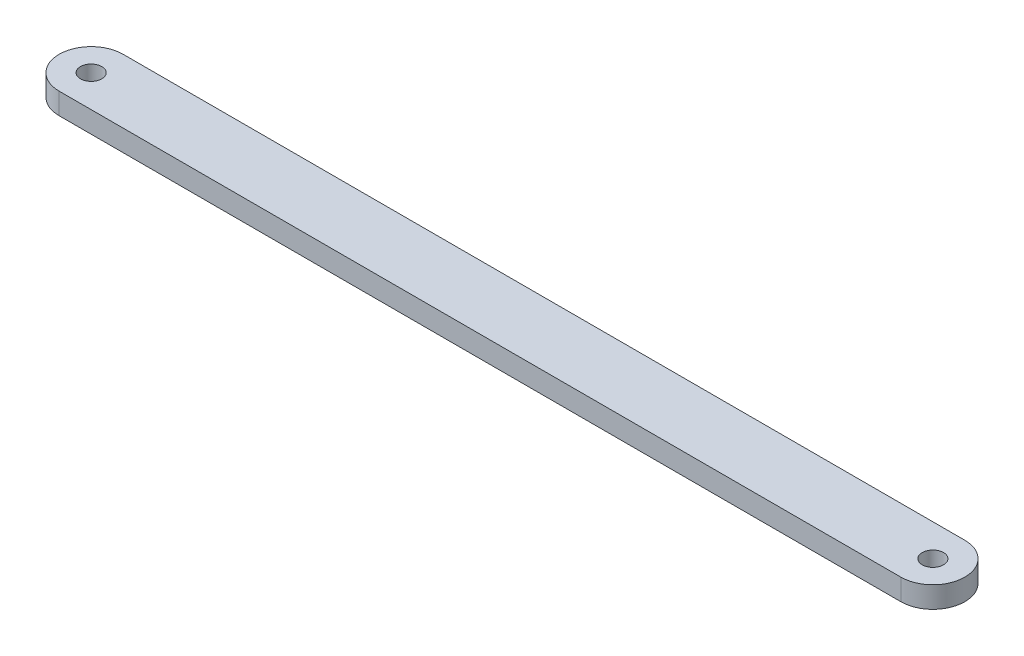
SolidWorks part; units mm, degrees
ref_plane "Front Plane" through (0, 0, 0) normal (0, 0, 1) x (1, 0, 0)
ref_plane "Top Plane" through (0, 0, 0) normal (0, 1, 0) x (1, 0, 0)
ref_plane "Right Plane" through (0, 0, 0) normal (1, 0, 0) x (0, 0, -1)
sketch "Sketch2" plane through (0, 0, 0) normal (0, 1, 0) x (1, 0, 0)
  line L0 (-197.5, 0) -> (197.5, 0) construction
  line L1 (-197.5, 15) -> (197.5, 15)
  line L2 (-197.5, -15) -> (197.5, -15)
  arc A0 (-197.5, 15) -> (-197.5, -15) centre (-197.5, 0) ccw
  arc A1 (197.5, -15) -> (197.5, 15) centre (197.5, 0) ccw
  circle A2 centre (-197.5, 0) radius 5
  circle A3 centre (197.5, 0) radius 5
  point P2 (0, 0)
  point P12 (0, -15)
  dimension "D1" = 10
  dimension "D2" = 10
  dimension "D3" = 395
  dimension "D4" = 30
extrude "Boss-Extrude1" add sketch "Sketch2" along normal blind 10
